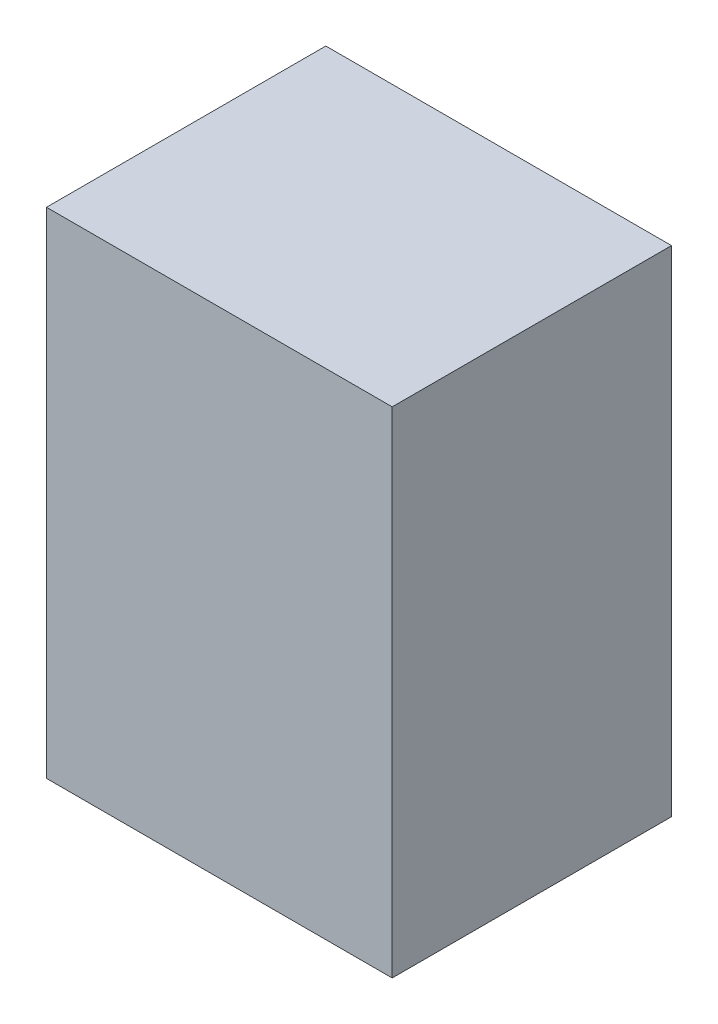
SolidWorks part; units mm, degrees
ref_plane "Front Plane" through (0, 0, 0) normal (0, 0, 1) x (1, 0, 0)
ref_plane "Top Plane" through (0, 0, 0) normal (0, 1, 0) x (1, 0, 0)
ref_plane "Right Plane" through (0, 0, 0) normal (1, 0, 0) x (0, 0, -1)
sketch "Sketch1" plane through (0, 0, 0) normal (0, 0, 1) x (1, 0, 0)
  line L1 (-109.4452, -28.4537) -> (475.2628, -28.4537)
  line L2 (-109.4452, -28.4537) -> (-109.4452, -865.1297)
  line L3 (-109.4452, -865.1297) -> (-96.7452, -865.1297)
  line L4 (475.2628, -28.4537) -> (475.2628, -865.1297)
  line L5 (462.5628, -865.1297) -> (475.2628, -865.1297)
  line L6 (-96.7452, -852.4297) -> (-96.7452, -865.1297)
  line L8 (-96.7452, -852.4297) -> (-96.7452, -41.1537)
  line L9 (-96.7452, -41.1537) -> (462.5628, -41.1537)
  line L10 (462.5628, -836.1737) -> (462.5628, -41.1537)
  line L13 (462.5628, -836.1737) -> (462.5628, -865.1297)
  dimension "D1" = 12.7
  dimension "D2" = 836.676
  dimension "D3" = 12.7
  dimension "D4" = 12.7
  dimension "D5" = 584.708
extrude "Boss-Extrude1" add sketch "Sketch1" along normal blind 457.2
sketch "Sketch2" plane through (0, 0, 457.2) normal (0, 0, 1) x (1, 0, 0)
  line L1 (-109.4452, -28.4537) -> (475.2628, -28.4537)
  line L2 (-109.4452, -28.4537) -> (-109.4452, -865.1297)
  line L3 (-109.4452, -865.1297) -> (475.2628, -865.1297)
  line L4 (475.2628, -28.4537) -> (475.2628, -865.1297)
extrude "Boss-Extrude2" add sketch "Sketch2" along normal blind 15.24
sketch "Sketch5" plane through (0, -41.1537, 0) normal (0, -1, 0) x (1, 0, 0)
  line L0 (182.9088, 0) -> (182.9088, 457.2) construction
  line L1 (-96.7452, 0) -> (462.5628, 0) construction
  line L2 (-96.7452, 457.2) -> (462.5628, 457.2) construction
